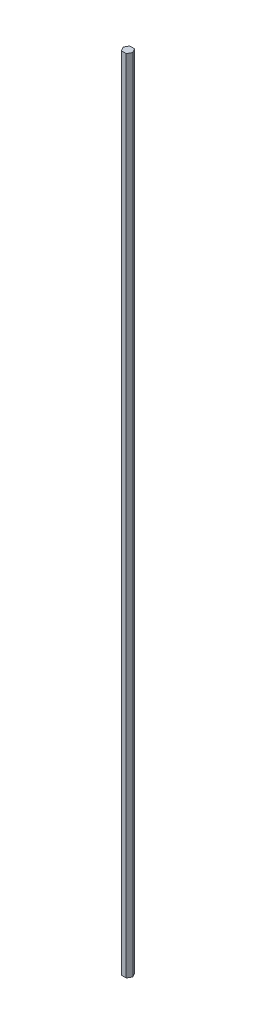
SolidWorks part; units mm, degrees
ref_plane "Front Plane" through (0, 0, 0) normal (0, 0, 1) x (1, 0, 0)
ref_plane "Top Plane" through (0, 0, 0) normal (0, 1, 0) x (1, 0, 0)
ref_plane "Right Plane" through (0, 0, 0) normal (1, 0, 0) x (0, 0, -1)
sketch "Sketch1" plane through (0, 0, 0) normal (0, 1, 0) x (1, 0, 0)
  line L1 (0.4695, -0.4472) -> (1.3859, 1.1404)
  line L2 (1.3859, 1.1404) -> (0.4692, 2.7278)
  line L3 (0.4692, 2.7278) -> (-1.3638, 2.7277)
  line L4 (-1.3638, 2.7277) -> (-2.2802, 1.1401)
  line L5 (-2.2802, 1.1401) -> (-1.3636, -0.4473)
  line L6 (-1.3636, -0.4473) -> (0.4695, -0.4472)
  circle A0 centre (-0.4472, 1.1403) radius 1.5875 construction
  dimension "D1" = 3.175
extrude "Boss-Extrude1" add sketch "Sketch1" along normal blind 304.8
